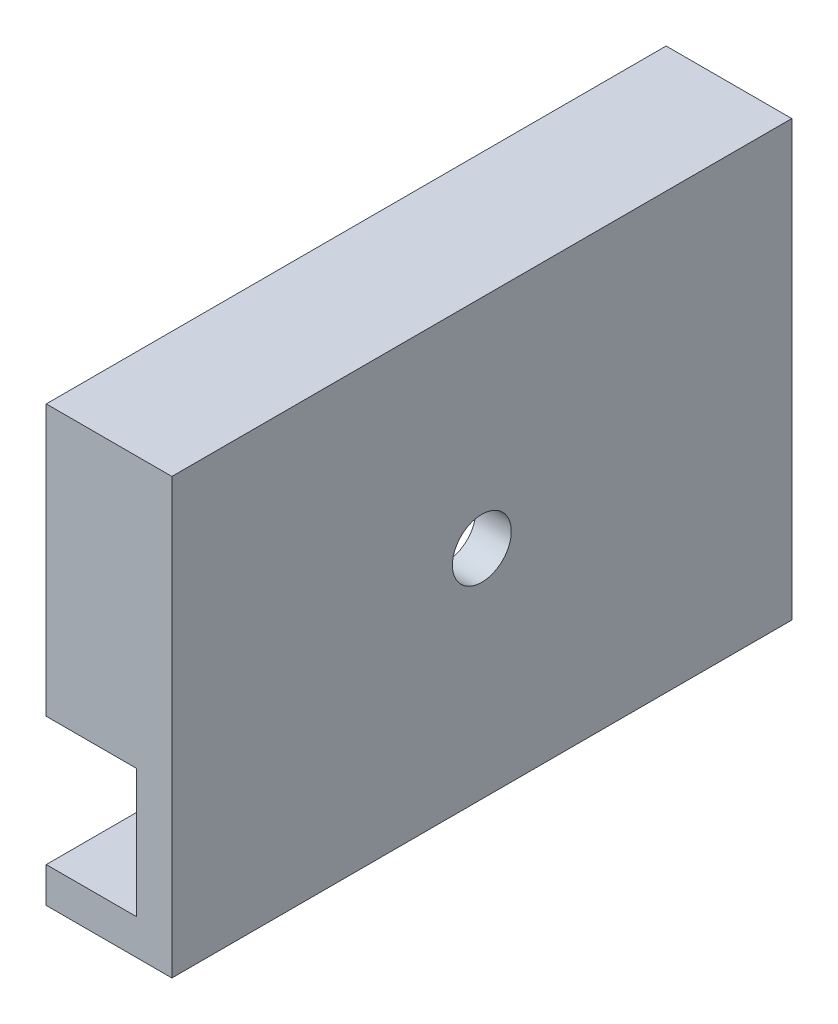
SolidWorks part; units mm, degrees
ref_plane "Front Plane" through (0, 0, 0) normal (0, 0, 1) x (1, 0, 0)
ref_plane "Top Plane" through (0, 0, 0) normal (0, 1, 0) x (1, 0, 0)
ref_plane "Right Plane" through (0, 0, 0) normal (1, 0, 0) x (0, 0, -1)
sketch "Sketch1" plane through (0, 0, 0) normal (0, 0, 1) x (1, 0, 0)
  line L1 (6.469, -26.0667) -> (-6.469, -26.0668)
  line L2 (6.469, -26.0667) -> (6.469, 26.0668)
  line L3 (6.469, 26.0668) -> (-6.469, 26.0668)
  line L5 (6.469, -26.0667) -> (-6.469, 26.0668) construction
  line L6 (6.469, 26.0668) -> (-6.469, -26.0668) construction
  point P0 (0, 0)
  dimension "D1" = 12.938
  dimension "D2" = 52.1335
extrude "Extrude-Thin1" add sketch "Sketch1" along normal blind 88.9 thin thin type one direction reverse wall 5.08
sketch "Sketch2" plane through (6.469, 0, 0) normal (-1, 0, 0) x (0, 0, 1)
  line L0 (44.45, 26.0668) -> (44.45, -26.0667) construction
  line L1 (88.9, 26.0668) -> (0, 26.0668) construction
  line L2 (88.9, -26.0667) -> (0, -26.0667) construction
  circle A0 centre (44.45, 0) radius 4.2227
  dimension "D1" = 8.4455
extrude "Cut-Extrude2" cut sketch "Sketch2" along direction (1, 0, 0) on the side against the normal up to surface (5.08 mm away)
sketch "Sketch3" plane through (0, 0, 88.9) normal (0, 0, 1) x (1, 0, 0)
  line L0 (11.549, 31.1468) -> (11.549, -31.1468) construction
  line L1 (-6.469, 31.1468) -> (11.549, 31.1468)
  line L2 (-6.469, 31.1468) -> (-6.469, -7.6518)
  line L3 (-6.469, -7.6518) -> (11.549, -7.6518)
  line L4 (11.549, 31.1468) -> (11.549, -7.6518)
  line L5 (6.469, -26.0667) -> (-6.469, -26.0668) construction
  point P7 (0, -26.0667)
  dimension "D1" = 18.415
extrude "Boss-Extrude1" add sketch "Sketch3" against normal blind 5.08
sketch "Sketch4" plane through (0, 0, 0) normal (0, 0, -1) x (-1, 0, 0)
  line L0 (6.469, 31.1468) -> (6.469, -7.6518) construction
  line L1 (-11.549, -31.1468) -> (6.469, -31.1468)
  line L2 (-11.549, -31.1468) -> (-11.549, 7.6518)
  line L3 (-11.549, 7.6518) -> (6.469, 7.6518)
  line L4 (6.469, -31.1468) -> (6.469, 7.6518)
  line L5 (6.469, 26.0668) -> (-6.469, 26.0668) construction
  dimension "D1" = 18.415
extrude "Boss-Extrude2" add sketch "Sketch4" against normal blind 5.08
